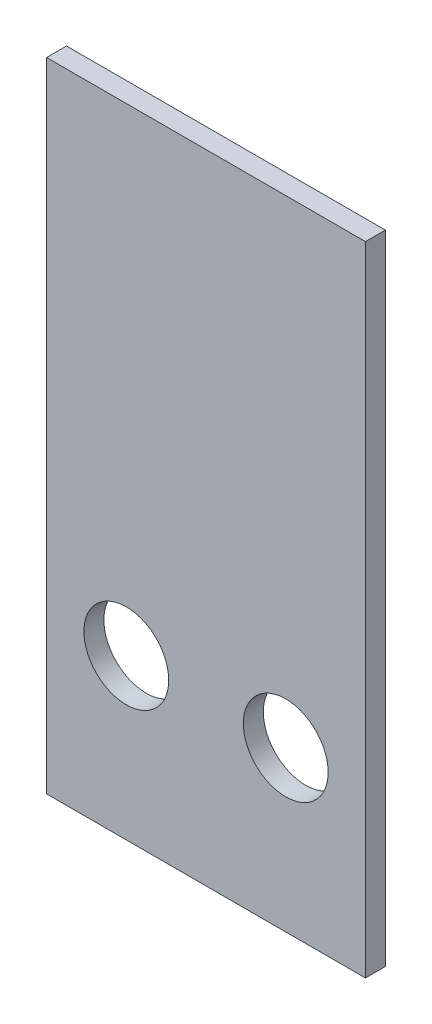
SolidWorks part; units mm, degrees
ref_plane "Front Plane" through (0, 0, 0) normal (0, 0, 1) x (1, 0, 0)
ref_plane "Top Plane" through (0, 0, 0) normal (0, 1, 0) x (1, 0, 0)
ref_plane "Right Plane" through (0, 0, 0) normal (1, 0, 0) x (0, 0, -1)
sketch "Sketch1" plane through (0, 0, 0) normal (0, 0, 1) x (1, 0, 0)
  line L1 (-12.7, 25.4) -> (12.7, 25.4)
  line L2 (-12.7, 25.4) -> (-12.7, -25.4)
  line L3 (-12.7, -25.4) -> (12.7, -25.4)
  line L4 (12.7, 25.4) -> (12.7, -25.4)
  line L5 (-12.7, 25.4) -> (12.7, -25.4) construction
  line L6 (-12.7, -25.4) -> (12.7, 25.4) construction
  point P0 (0, 0)
  dimension "D1" = 50.8
  dimension "D2" = 25.4
extrude "Boss-Extrude1" add sketch "Sketch1" along normal blind 1.5875
sketch "Sketch2" plane through (0, 0, 1.5875) normal (0, 0, 1) x (1, 0, 0)
  line L0 (-12.7, -25.4) -> (12.7, -25.4) construction
  line L1 (-12.7, 25.4) -> (-12.7, -25.4) construction
  point P0 (-6.35, -12.7)
  point P1 (6.35, -12.7)
  point P2 (0, 0)
  dimension "D1" = 12.7
  dimension "D2" = 12.7
  dimension "D3" = 6.35
hole_wizard "1/4 Clearance Hole1" positions "Sketch3" profile "Sketch4" hole size "1/4" standard "ANSI Inch" end condition through all
sketch "Sketch3" plane through (0, 0, 1.5875) normal (0, 0, 1) x (1, 0, 0)
  point P0 (-6.35, -12.7)
  point P3 (6.35, -12.7)
sketch "Sketch4" plane through (-6.35, -12.7, 1.5875) normal (1, 0, 0) x (0, -1, 0)
  line L0 (0, 0) -> (0, 1.5875)
  line L1 (0, 1.5875) -> (3.3782, 1.5875)
  line L2 (3.3782, 1.5875) -> (3.3782, 0)
  line L5 (3.3782, 0) -> (0, 0)
  line L11 (0, -6.35) -> (0, 107.95) construction
  dimension "Thru Hole Dia." = 6.7564
  dimension "Thru Hole Depth" = 1.5875
